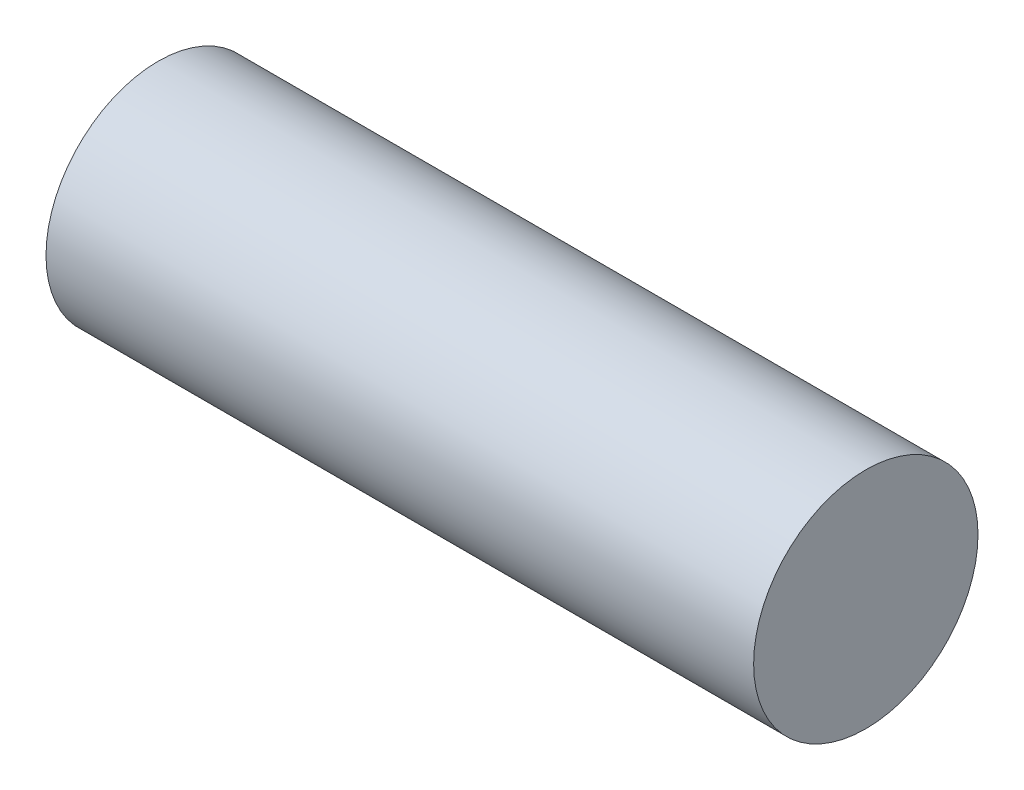
SolidWorks part; units mm, degrees
ref_plane "Front Plane" through (0, 0, 0) normal (0, 0, 1) x (1, 0, 0)
ref_plane "Top Plane" through (0, 0, 0) normal (0, 1, 0) x (1, 0, 0)
ref_plane "Right Plane" through (0, 0, 0) normal (1, 0, 0) x (0, 0, -1)
sketch "Sketch1" plane through (0, 0, 0) normal (1, 0, 0) x (0, 0, -1)
  circle A0 centre (0, 0) radius 6.5
  dimension "D1" = 13
extrude "Base" add sketch "Sketch1" along normal mid plane 41
